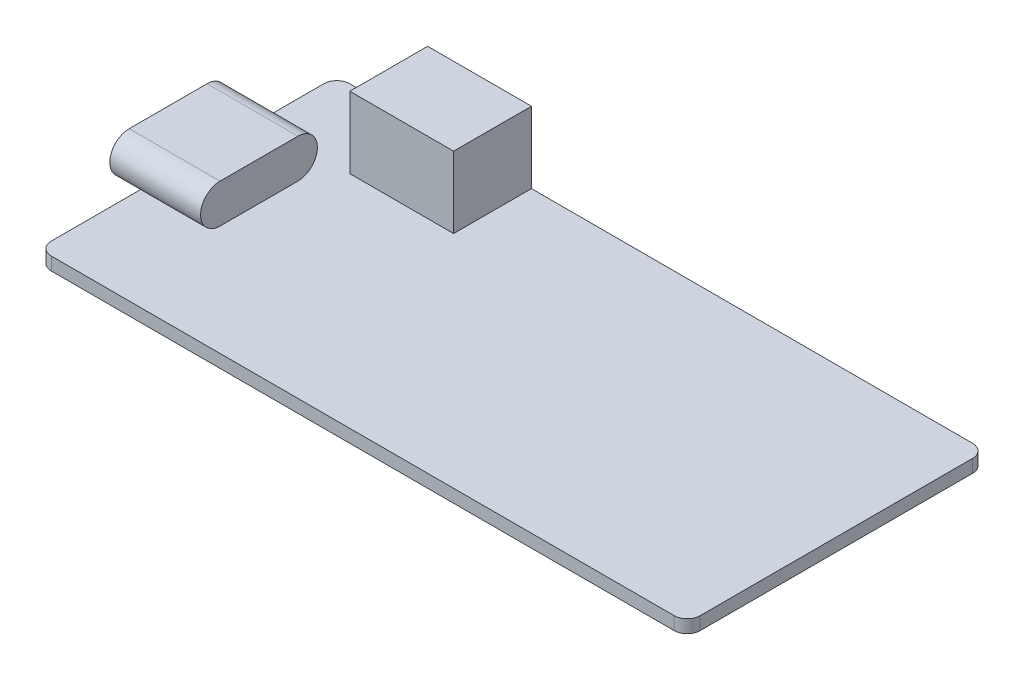
SolidWorks part; units mm, degrees
ref_plane "Front Plane" through (0, 0, 0) normal (0, 0, 1) x (1, 0, 0)
ref_plane "Top Plane" through (0, 0, 0) normal (0, 1, 0) x (1, 0, 0)
ref_plane "Right Plane" through (0, 0, 0) normal (1, 0, 0) x (0, 0, -1)
sketch "Sketch1" plane through (0, 0, 0) normal (0, 1, 0) x (1, 0, 0)
  line L1 (0, 0) -> (50, 0)
  line L2 (0, 0) -> (0, 23)
  line L3 (0, 23) -> (50, 23)
  line L4 (50, 0) -> (50, 23)
extrude "Boss-Extrude1" add sketch "Sketch1" along normal blind 1
fillet "Fillet1" radius 1 4 edges at (50, 0.5, 0) (50, 0.5, -23) (0, 0.5, -23) (0, 0.5, 0)
sketch "Sketch2" plane through (0, 0, 0) normal (-1, 0, 0) x (0, 0, 1)
  line L0 (-8.5, 2.5) -> (-14.5, 2.5) construction
  line L1 (-8.5, 1) -> (-14.5, 1)
  line L2 (-8.5, 4) -> (-14.5, 4)
  line L3 (-22, 1) -> (-1, 1) construction
  arc A0 (-8.5, 1) -> (-8.5, 4) centre (-8.5, 2.5) ccw
  arc A1 (-14.5, 4) -> (-14.5, 1) centre (-14.5, 2.5) ccw
  point P2 (-11.5, 2.5)
  dimension "D1" = 11.5
  dimension "D2" = 1.5
extrude "Boss-Extrude2" add sketch "Sketch2" along normal blind 1.5 and the other way blind 5.5
sketch "Sketch3" plane through (0, 1, 0) normal (0, 1, 0) x (1, 0, 0)
  line L0 (49, 23) -> (1, 23) construction
  line L1 (7, 23) -> (15, 23)
  line L2 (7, 23) -> (7, 17)
  line L3 (7, 17) -> (15, 17)
  line L4 (15, 23) -> (15, 17)
  line L5 (0, 22) -> (0, 14.5) construction
  dimension "D1" = 8
  dimension "D2" = 6
  dimension "D3" = 7
extrude "Boss-Extrude3" add sketch "Sketch3" along normal blind 5.5
